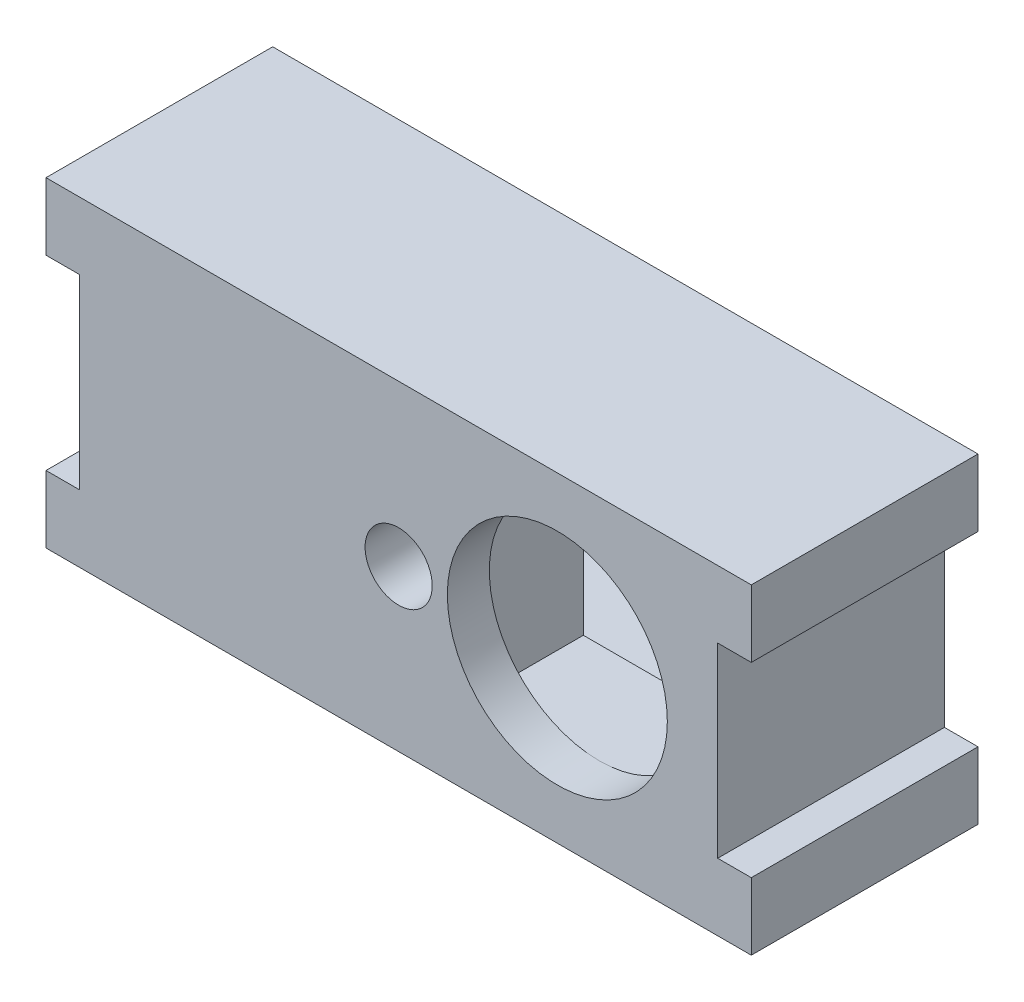
SolidWorks part; units mm, degrees
ref_plane "Front Plane" through (0, 0, 0) normal (0, 0, 1) x (1, 0, 0)
ref_plane "Top Plane" through (0, 0, 0) normal (0, 1, 0) x (1, 0, 0)
ref_plane "Right Plane" through (0, 0, 0) normal (1, 0, 0) x (0, 0, -1)
sketch "Sketch2" plane through (0, 0, 0) normal (0, 0, 1) x (1, 0, 0)
  line L0 (-19, 9.55) -> (-19, -9.55)
  line L1 (-16, 6.55) -> (16, 6.55) construction
  line L2 (-16, 6.55) -> (-16, -6.55) construction
  line L3 (-16, -6.55) -> (16, -6.55) construction
  line L4 (16, 6.55) -> (16, -6.55) construction
  line L5 (-16, 6.55) -> (16, -6.55) construction
  line L6 (-16, -6.55) -> (16, 6.55) construction
  line L7 (-19, -9.55) -> (19, -9.55)
  line L8 (19, 9.55) -> (19, -9.55)
  line L9 (-19, 9.55) -> (19, 9.55)
  circle A0 centre (9.45, 0) radius 6.55
  circle A1 centre (0, 0) radius 2
  point P0 (0, 0)
  point P15 (-16, 0)
  dimension "D5" = 4
  dimension "D1" = 32
  dimension "D2" = 13.1
  dimension "D4" = 16
  dimension "D3" = 3
extrude "Boss-Extrude1" add sketch "Sketch2" against normal blind 2.5
sketch "Sketch3" plane through (0, 0, -2.5) normal (0, 0, -1) x (-1, 0, 0)
  line L0 (-2.5, 6.55) -> (-2.5, -6.55)
  line L1 (19, 9.55) -> (-19, 9.55) construction
  line L2 (19, -9.55) -> (-19, -9.55) construction
  line L3 (-19, -9.55) -> (19, -9.55)
  line L4 (19, -9.55) -> (19, -5.55)
  line L5 (19, -5.55) -> (2.5, -5.55)
  line L6 (2.5, -5.55) -> (2.5, 5.55)
  line L7 (2.5, 5.55) -> (19, 5.55)
  line L9 (19, 9.55) -> (-19, 9.55)
  line L10 (19, 9.55) -> (19, -9.55) construction
  line L11 (16, 6.55) -> (-16, 6.55) construction
  line L12 (-2.5, 6.55) -> (-16, 6.55)
  line L13 (-16, 6.55) -> (-16, -6.55) construction
  line L14 (-16, 6.55) -> (-16, -6.55)
  line L16 (19, 9.55) -> (19, 5.55)
  line L17 (-2.5, -6.55) -> (-16, -6.55)
  line L18 (-19, 9.55) -> (-19, -9.55)
  line L19 (16, -6.55) -> (-16, -6.55) construction
  circle A0 centre (0, 0) radius 2 construction
  circle A1 centre (0, 0) radius 2
  dimension "D1" = 1
  dimension "D2" = 1
  dimension "D3" = 2.5
  dimension "D4" = 5
extrude "Boss-Extrude2" add sketch "Sketch3" along normal blind 6
sketch "Sketch4" plane through (0, 0, -8.5) normal (0, 0, -1) x (-1, 0, 0)
  line L4 (19, 5.55) -> (16.5, 5.55)
  line L5 (-19, -9.55) -> (19, -9.55)
  line L6 (-19, -9.55) -> (-19, 9.55)
  line L7 (-19, 9.55) -> (19, 9.55)
  line L8 (16.5, -7.05) -> (16.5, 7.05)
  line L9 (-16.5, -7.05) -> (16.5, -7.05)
  line L10 (-16.5, 7.05) -> (-16.5, -7.05)
  line L11 (16.5, 7.05) -> (-16.5, 7.05)
  line L12 (16.5, -7.05) -> (16.5, -5.55)
  line L13 (-16.5, -7.05) -> (16.5, -7.05)
  line L14 (-16.5, 7.05) -> (-16.5, -7.05)
  line L15 (16.5, 7.05) -> (-16.5, 7.05)
  line L16 (19, -9.55) -> (19, -5.55)
  line L17 (19, -5.55) -> (16.5, -5.55)
  line L18 (16.5, 5.55) -> (16.5, 7.05)
  line L19 (19, 5.55) -> (19, 9.55)
  dimension "D1" = 0.5
extrude "Boss-Extrude3" add sketch "Sketch4" along normal blind 5
sketch "Sketch5" plane through (0, 0, -13.5) normal (0, 0, -1) x (-1, 0, 0)
  line L0 (-19, 9.55) -> (-21, 9.55)
  line L1 (-19, 9.55) -> (-19, -9.55) construction
  line L2 (-21, 9.55) -> (-21, 5.55)
  line L3 (-21, 5.55) -> (-19, 5.55)
  line L4 (-19, 5.55) -> (-19, 9.55)
  line L6 (7.425, 0) -> (-7.425, 0) construction
  line L7 (-19, -5.55) -> (-19, -9.55)
  line L8 (-21, -9.55) -> (-21, -5.55)
  line L9 (-21, -5.55) -> (-19, -5.55)
  line L10 (-19, -9.55) -> (-21, -9.55)
  point P4 (-19, 9.55)
  dimension "D1" = 4
  dimension "D4" = 2
extrude "Boss-Extrude4" add sketch "Sketch5" against normal up to surface (13.5 mm away) up to face at (2, 0, 0)
mirror "Mirror1" about plane through (0, 0, 0) normal (1, 0, 0) of "Boss-Extrude4"
